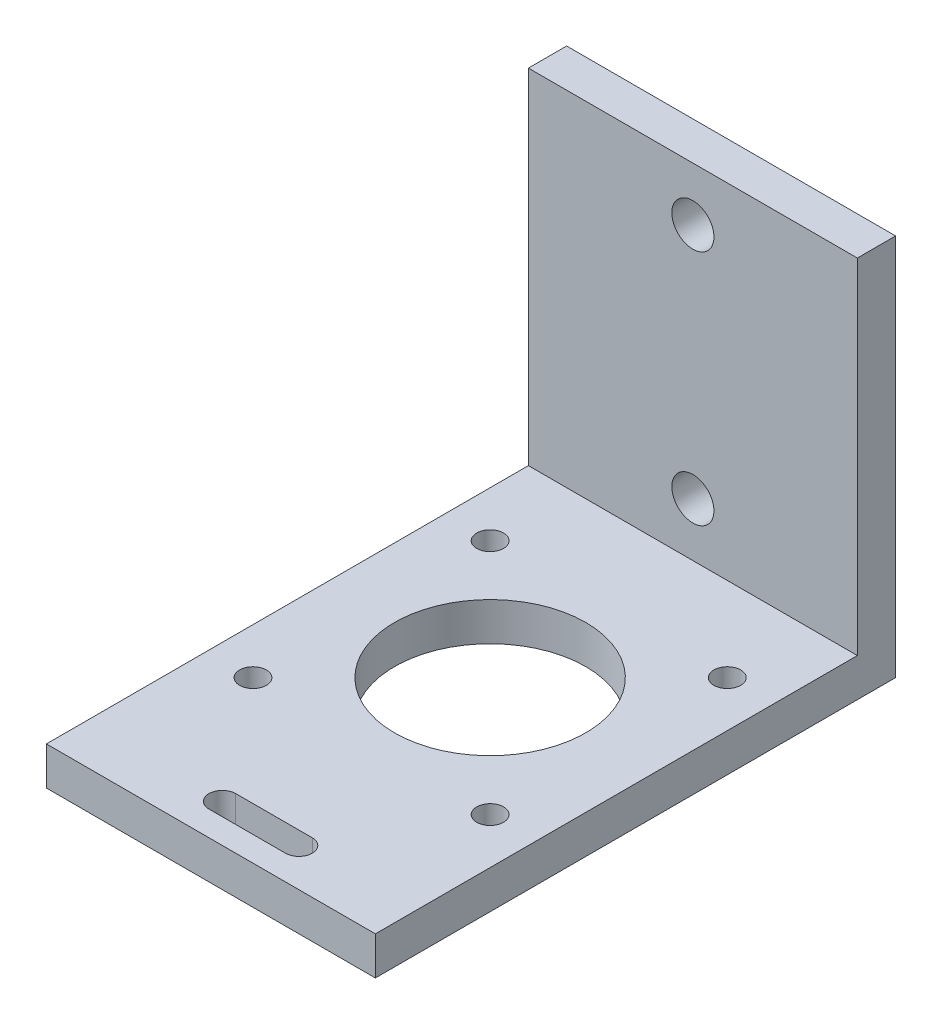
SolidWorks part; units mm, degrees
ref_plane "前视基准面" through (0, 0, 0) normal (0, 0, 1) x (1, 0, 0)
ref_plane "上视基准面" through (0, 0, 0) normal (0, 1, 0) x (1, 0, 0)
ref_plane "右视基准面" through (0, 0, 0) normal (1, 0, 0) x (0, 0, -1)
sketch "草图1" plane through (0, 0, 0) normal (0, 1, 0) x (1, 0, 0)
  line L1 (-35.8997, 33.2122) -> (7.1003, 33.2122)
  line L2 (-35.8997, 33.2122) -> (-35.8997, -9.7878)
  line L3 (-35.8997, -9.7878) -> (7.1003, -9.7878)
  line L4 (7.1003, 33.2122) -> (7.1003, -9.7878)
  line L5 (-14.3997, -9.7878) -> (-14.3997, 33.2122) construction
  line L6 (-35.8997, 11.7122) -> (7.1003, 11.7122) construction
  line L7 (-29.8997, 27.2122) -> (1.1003, 27.2122) construction
  line L8 (-29.8997, 27.2122) -> (-29.8997, -3.7878) construction
  line L9 (-29.8997, -3.7878) -> (1.1003, -3.7878) construction
  line L10 (1.1003, 27.2122) -> (1.1003, -3.7878) construction
  line L11 (-14.3997, -3.7878) -> (-14.3997, 27.2122) construction
  line L12 (-29.8997, 11.7122) -> (1.1003, 11.7122) construction
  circle A0 centre (1.1003, 27.2122) radius 1.75
  circle A1 centre (-29.8997, 27.2122) radius 1.75
  circle A2 centre (-29.8997, -3.7878) radius 1.75
  circle A3 centre (1.1003, -3.7878) radius 1.75
  circle A4 centre (-14.3997, 11.7122) radius 12.5
  point P0 (-14.3997, 11.7122)
  point P4 (-14.3997, 11.7122)
  dimension "D4" = 3.5
  dimension "D5" = 25
  dimension "D1" = 43
  dimension "D2" = 43
  dimension "D3" = 31
extrude "凸台-拉伸1" add sketch "草图1" along normal blind 5
sketch "草图3" plane through (0, 0, -33.2122) normal (0, 0, -1) x (-1, 0, 0)
  line L4 (-7.1003, 0) -> (35.8997, 0)
  line L5 (35.8997, 0) -> (35.8997, 5)
  line L6 (35.8997, 5) -> (-7.1003, 5)
  line L7 (-7.1003, 5) -> (-7.1003, 0)
  line L8 (-7.1003, 0) -> (35.8997, 0)
  line L9 (35.8997, 0) -> (35.8997, 5)
  line L10 (35.8997, 5) -> (-7.1003, 5)
  line L11 (-7.1003, 5) -> (-7.1003, 0)
  dimension "D1" = 0
extrude "凸台-拉伸2" add sketch "草图3" along normal blind 5
sketch "草图4" plane through (0, 0, -38.2122) normal (0, 0, -1) x (-1, 0, 0)
  line L1 (35.8997, 0) -> (-7.1003, 0)
  line L2 (35.8997, 0) -> (35.8997, 50)
  line L3 (35.8997, 50) -> (-7.1003, 50)
  line L4 (-7.1003, 0) -> (-7.1003, 50)
  line L5 (35.8997, 0) -> (-7.1003, 50) construction
  line L6 (35.8997, 50) -> (-7.1003, 0) construction
  point P4 (14.3997, 25)
  dimension "D1" = 50
extrude "凸台-拉伸3" add sketch "草图4" along normal blind 5
sketch "草图5" plane through (0, 0, -38.2122) normal (0, 0, 1) x (1, 0, 0)
  line L0 (-14.3997, 50) -> (-14.3997, 0) construction
  line L1 (-35.8997, 50) -> (7.1003, 50) construction
  line L2 (7.1003, 0) -> (-35.8997, 0) construction
  line L3 (-35.8997, 5) -> (7.1003, 5) construction
  line L4 (-35.8997, 50) -> (7.1003, 50) construction
  circle A0 centre (-14.3997, 43) radius 2.75
  circle A1 centre (-14.3997, 12) radius 2.75
  dimension "D1" = 5.5
  dimension "D2" = 5.5
  dimension "D3" = 7
  dimension "D4" = 7
extrude "切除-拉伸1" cut sketch "草图5" against normal through all
sketch "草图6" plane through (0, 0, 9.7878) normal (0, 0, 1) x (1, 0, 0)
  line L4 (-35.8997, 0) -> (7.1003, 0)
  line L5 (7.1003, 0) -> (7.1003, 5)
  line L6 (7.1003, 5) -> (-35.8997, 5)
  line L7 (-35.8997, 5) -> (-35.8997, 0)
  line L8 (-35.8997, 0) -> (7.1003, 0)
  line L9 (7.1003, 0) -> (7.1003, 5)
  line L10 (7.1003, 5) -> (-35.8997, 5)
  line L11 (-35.8997, 5) -> (-35.8997, 0)
  dimension "D1" = 0
extrude "凸台-拉伸4" add sketch "草图6" along normal blind 15
sketch "草图7" plane through (0, 5, 0) normal (0, 1, 0) x (1, 0, 0)
  line L0 (-17.8997, -19.7878) -> (2.1003, -19.7878) construction
  line L1 (-17.8997, -19.7878) -> (-7.8997, -19.7878) construction
  line L2 (-17.8997, -18.0378) -> (-7.8997, -18.0378)
  line L3 (-17.8997, -21.5378) -> (-7.8997, -21.5378)
  arc A0 (-17.8997, -18.0378) -> (-17.8997, -21.5378) centre (-17.8997, -19.7878) ccw
  arc A1 (-7.8997, -21.5378) -> (-7.8997, -18.0378) centre (-7.8997, -19.7878) ccw
  point P5 (-12.8997, -19.7878)
  dimension "D1" = 3.5
  dimension "D2" = 10
extrude "切除-拉伸2" cut sketch "草图7" against normal through all
